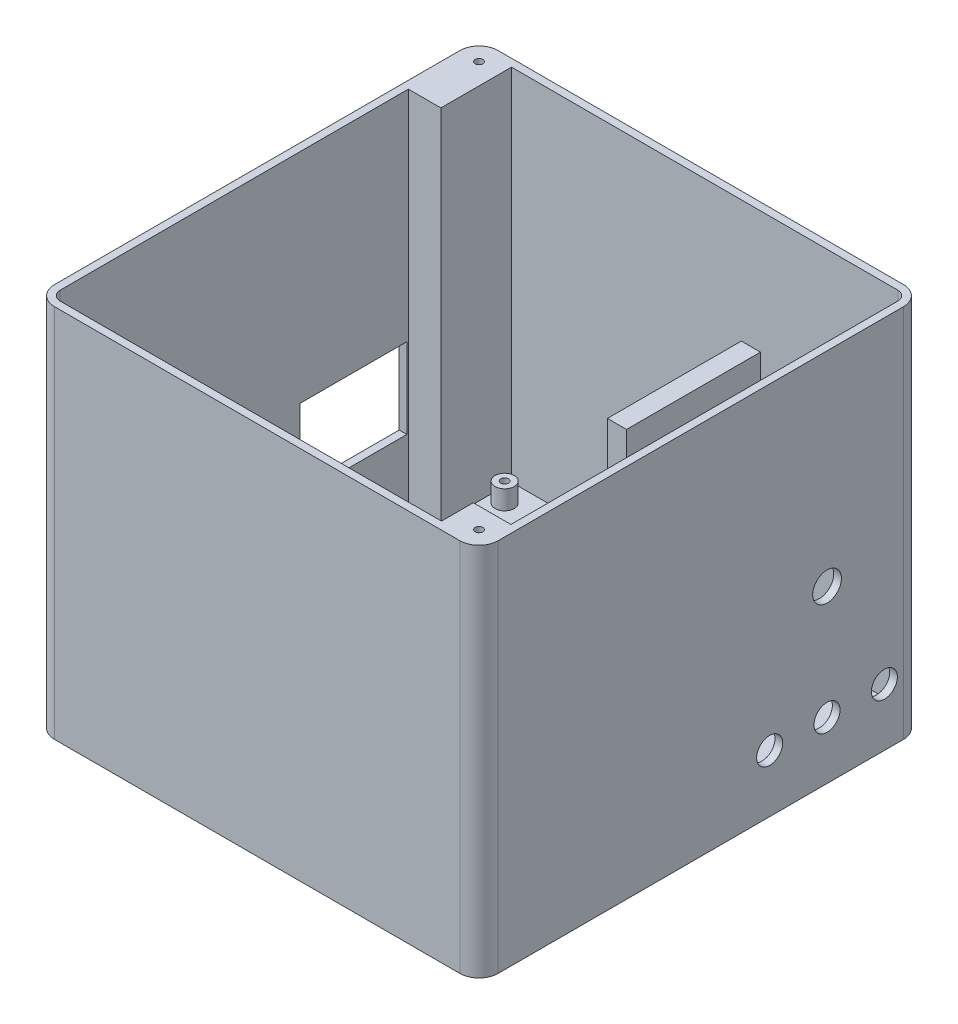
SolidWorks part; units mm, degrees
ref_plane "Front Plane" through (0, 0, 0) normal (0, 0, 1) x (1, 0, 0)
ref_plane "Top Plane" through (0, 0, 0) normal (0, 1, 0) x (1, 0, 0)
ref_plane "Right Plane" through (0, 0, 0) normal (1, 0, 0) x (0, 0, -1)
sketch "Sketch3" plane through (0, 0, 0) normal (0, 1, 0) x (1, 0, 0)
  line L1 (56, 56) -> (-56, 56)
  line L2 (56, 56) -> (56, -56)
  line L3 (56, -56) -> (-56, -56)
  line L4 (-56, 56) -> (-56, -56)
  line L5 (56, 56) -> (-56, -56) construction
  line L6 (56, -56) -> (-56, 56) construction
  point P0 (0, 0)
  dimension "D1" = 112
  dimension "D2" = 112
extrude "Extrude-Thin1" add sketch "Sketch3" along normal blind 98 thin
sketch "Sketch7" plane through (-56, 0, 0) normal (1, 0, 0) x (0, 0, -1)
  line L0 (56, 98) -> (56, 0) construction
  line L1 (-56, 0) -> (56, 0)
  line L2 (-56, 0) -> (-56, 4)
  line L3 (-56, 4) -> (56, 4)
  line L4 (56, 0) -> (56, 4)
  line L5 (56, 0) -> (-56, 0) construction
  dimension "D1" = 4
extrude "Boss-Extrude1" add sketch "Sketch7" along normal up to surface (112 mm away) up to face at (56, 49, 0)
sketch "Sketch13" plane through (0, 4, 0) normal (0, 1, 0) x (1, 0, 0)
  line L1 (39.1589, 5.1688) -> (-53.8411, 5.1688)
  line L2 (39.1589, 5.1688) -> (39.1589, -54.8312)
  line L3 (39.1589, -54.8312) -> (-53.8411, -54.8312)
  line L4 (-53.8411, 5.1688) -> (-53.8411, -54.8312)
  line L5 (39.1589, 5.1688) -> (-53.8411, -54.8312) construction
  line L6 (39.1589, -54.8312) -> (-53.8411, 5.1688) construction
  point P0 (-7.3411, -24.8312)
  dimension "D1" = 60
  dimension "D2" = 93
sketch "Sketch15" plane through (0, 4, 0) normal (0, 1, 0) x (1, 0, 0)
  line L1 (10.8366, 52.9269) -> (-46.1634, 52.9269)
  line L2 (10.8366, 52.9269) -> (10.8366, 9.3669)
  line L3 (10.8366, 9.3669) -> (-46.1634, 9.3669)
  line L4 (-46.1634, 52.9269) -> (-46.1634, 9.3669)
  line L5 (10.8366, 52.9269) -> (-46.1634, 9.3669) construction
  line L6 (10.8366, 9.3669) -> (-46.1634, 52.9269) construction
  point P0 (-17.6634, 31.1469)
  dimension "D1" = 57
  dimension "D2" = 43.56
sketch "Sketch16" plane through (0, 4, 0) normal (0, 1, 0) x (1, 0, 0)
  line L0 (-46.1634, 52.9269) -> (-46.1634, 9.3669) construction
  line L1 (10.8366, 9.3669) -> (-46.1634, 9.3669) construction
  circle A0 centre (-43.6634, 11.8669) radius 2.5
  circle A1 centre (8.3366, 11.8669) radius 2.5
  circle A2 centre (8.3366, 50.3669) radius 2.5
  circle A3 centre (-43.6634, 50.3669) radius 2.5
  dimension "D3" = 5
  dimension "D1" = 2.5
  dimension "D2" = 2.5
  dimension "D4" = 2
  dimension "D5" = 2
extrude "Boss-Extrude5" add sketch "Sketch16" along normal blind 5
sketch "Sketch17" plane through (0, 9, 0) normal (0, 1, 0) x (1, 0, 0)
  circle A0 centre (8.3366, 11.8669) radius 1
  circle A1 centre (-43.6634, 11.8669) radius 1
  circle A2 centre (-43.6634, 50.3669) radius 1
  circle A3 centre (8.3366, 50.3669) radius 1
  dimension "D1" = 2
  dimension "D2" = 2
  dimension "D3" = 2
extrude "Cut-Extrude1" cut sketch "Sketch17" against normal blind 10
sketch "Sketch24" plane through (-58, 0, 0) normal (-1, 0, 0) x (0, 0, 1)
  line L1 (-37.1281, 41) -> (-9.1281, 41)
  line L2 (-37.1281, 41) -> (-37.1281, 20)
  line L3 (-37.1281, 20) -> (-9.1281, 20)
  line L4 (-9.1281, 41) -> (-9.1281, 20)
  line L5 (-37.1281, 41) -> (-9.1281, 20) construction
  line L6 (-37.1281, 20) -> (-9.1281, 41) construction
  line L8 (-58, 0) -> (58, 0) construction
  point P0 (-23.1281, 30.5)
  dimension "D1" = 28
  dimension "D2" = 21
  dimension "D3" = 20
extrude "Cut-Extrude5" cut sketch "Sketch24" against normal blind 3
sketch "Sketch25" plane through (58, 0, 0) normal (1, 0, 0) x (0, 0, -1)
  line L0 (58, 0) -> (58, 15)
  line L1 (58, 98) -> (58, 0) construction
  circle A0 centre (48, 15) radius 3.4
  circle A1 centre (33, 15) radius 3.4
  circle A2 centre (18, 15) radius 3.4
  dimension "D2" = 6.8
  dimension "D3" = 6.8
  dimension "D4" = 6.8
  dimension "D1" = 15
  dimension "D5" = 10
  dimension "D6" = 15
  dimension "D7" = 15
extrude "Cut-Extrude6" cut sketch "Sketch25" against normal blind 5 contours A2 | A1 | A0
sketch "Sketch26" plane through (-58, 0, 0) normal (-1, 0, 0) x (0, 0, 1)
  line L1 (-37.1281, 41) -> (-9.1281, 41)
  line L2 (-37.1281, 41) -> (-37.1281, 20)
  line L3 (-37.1281, 20) -> (-9.1281, 20)
  line L4 (-9.1281, 41) -> (-9.1281, 20)
  line L5 (1.8719, 42.1305) -> (-48.1281, 42.1305)
  line L6 (1.8719, 42.1305) -> (1.8719, 19.1305)
  line L7 (1.8719, 19.1305) -> (-48.1281, 19.1305)
  line L8 (-48.1281, 42.1305) -> (-48.1281, 19.1305)
  line L9 (1.8719, 42.1305) -> (-48.1281, 19.1305) construction
  line L10 (1.8719, 19.1305) -> (-48.1281, 42.1305) construction
  circle A0 centre (-42.7671, 30.6305) radius 2
  circle A1 centre (-2.7671, 30.6305) radius 2
  point P6 (-23.1281, 30.6305)
  dimension "D3" = 4
  dimension "D4" = 4
  dimension "D1" = 50
  dimension "D2" = 23
  dimension "D5" = 40
extrude "Cut-Extrude7" cut sketch "Sketch26" against normal blind 10 contours A0 | A1
fillet "Fillet1" radius 5 4 edges at (-58, 49, 58) (-58, 49, -58) (58, 49, -58) (58, 49, 58)
sketch "Sketch28" plane through (0, 0, 0) normal (0, -1, 0) x (1, 0, 0)
  circle A0 centre (-53.8411, 54.8312) radius 1
  circle A1 centre (-43.8411, 54.8312) radius 1
  circle A2 centre (-33.8411, 54.8312) radius 1
  circle A3 centre (-23.8411, 54.8312) radius 1
  circle A4 centre (-13.8411, 54.8312) radius 1
  circle A5 centre (-3.8411, 54.8312) radius 1
  circle A6 centre (6.1589, 54.8312) radius 1
  circle A7 centre (16.1589, 54.8312) radius 1
  circle A8 centre (26.1589, 54.8312) radius 1
  circle A9 centre (36.1589, 54.8312) radius 1
  circle A10 centre (-43.8411, 44.8312) radius 1
  circle A11 centre (-33.8411, 44.8312) radius 1
  circle A12 centre (-23.8411, 44.8312) radius 1
  circle A13 centre (-13.8411, 44.8312) radius 1
  circle A14 centre (-3.8411, 44.8312) radius 1
  circle A15 centre (6.1589, 44.8312) radius 1
  circle A16 centre (16.1589, 44.8312) radius 1
  circle A17 centre (26.1589, 44.8312) radius 1
  circle A18 centre (36.1589, 44.8312) radius 1
  circle A19 centre (-43.8411, 34.8312) radius 1
  circle A20 centre (-33.8411, 34.8312) radius 1
  circle A21 centre (-23.8411, 34.8312) radius 1
  circle A22 centre (-13.8411, 34.8312) radius 1
  circle A23 centre (-3.8411, 34.8312) radius 1
  circle A24 centre (6.1589, 34.8312) radius 1
  circle A25 centre (16.1589, 34.8312) radius 1
  circle A26 centre (26.1589, 34.8312) radius 1
  circle A27 centre (36.1589, 34.8312) radius 1
  circle A28 centre (-43.8411, 24.8312) radius 1
  circle A29 centre (-33.8411, 24.8312) radius 1
  circle A30 centre (-23.8411, 24.8312) radius 1
  circle A31 centre (-13.8411, 24.8312) radius 1
  circle A32 centre (-3.8411, 24.8312) radius 1
  circle A33 centre (6.1589, 24.8312) radius 1
  circle A34 centre (16.1589, 24.8312) radius 1
  circle A35 centre (26.1589, 24.8312) radius 1
  circle A36 centre (36.1589, 24.8312) radius 1
  circle A37 centre (-43.8411, 14.8312) radius 1
  circle A38 centre (-33.8411, 14.8312) radius 1
  circle A39 centre (-23.8411, 14.8312) radius 1
  circle A40 centre (-13.8411, 14.8312) radius 1
  circle A41 centre (-3.8411, 14.8312) radius 1
  circle A42 centre (6.1589, 14.8312) radius 1
  circle A43 centre (16.1589, 14.8312) radius 1
  circle A44 centre (26.1589, 14.8312) radius 1
  circle A45 centre (36.1589, 14.8312) radius 1
  circle A46 centre (-43.8411, 4.8312) radius 1
  circle A47 centre (-33.8411, 4.8312) radius 1
  circle A48 centre (-23.8411, 4.8312) radius 1
  circle A49 centre (-13.8411, 4.8312) radius 1
  circle A50 centre (-3.8411, 4.8312) radius 1
  circle A51 centre (6.1589, 4.8312) radius 1
  circle A52 centre (16.1589, 4.8312) radius 1
  circle A53 centre (26.1589, 4.8312) radius 1
  circle A54 centre (36.1589, 4.8312) radius 1
  circle A55 centre (-43.8411, -5.1688) radius 1
  circle A56 centre (-33.8411, -5.1688) radius 1
  circle A57 centre (-23.8411, -5.1688) radius 1
  circle A58 centre (-13.8411, -5.1688) radius 1
  circle A59 centre (-3.8411, -5.1688) radius 1
  circle A60 centre (6.1589, -5.1688) radius 1
  circle A61 centre (16.1589, -5.1688) radius 1
  circle A62 centre (26.1589, -5.1688) radius 1
  circle A63 centre (36.1589, -5.1688) radius 1
  circle A64 centre (-53.8411, 44.8312) radius 1
  circle A65 centre (-53.8411, 34.8312) radius 1
  circle A66 centre (-53.8411, 24.8312) radius 1
  circle A67 centre (-53.8411, 14.8312) radius 1
  circle A68 centre (-53.8411, 4.8312) radius 1
  circle A69 centre (-53.8411, -5.1688) radius 1
  dimension "D1" = 2
  dimension "D2" = 10
  dimension "D3" = 7
extrude "Cut-Extrude8" cut sketch "Sketch28" against normal blind 5
sketch "Sketch29" plane through (0, 4, 0) normal (0, 1, 0) x (1, 0, 0)
  line L0 (39.1589, 5.1688) -> (30.0023, 5.1688)
  line L1 (39.1589, 5.1688) -> (-53.8411, 5.1688) construction
  line L2 (30.0023, 5.1688) -> (30.0023, 9.7954)
  line L3 (30.0023, 9.7954) -> (53.3852, 9.7954)
  line L4 (53.3852, 9.7954) -> (53.3852, -6.0279)
  line L5 (53.3852, -6.0279) -> (39.1589, -6.0279)
  line L6 (39.1589, 5.1688) -> (39.1589, -54.8312) construction
  line L7 (39.1589, -6.0279) -> (39.1589, 5.1688)
  line L8 (39.1589, -6.1727) -> (56.512, -6.1727)
  line L9 (56.512, -6.1727) -> (56.512, -56)
  line L10 (-56, -56) -> (56, -56) construction
  line L11 (56.512, -56) -> (39.1589, -56)
  line L12 (39.1589, -56) -> (39.1589, -6.1727)
extrude "Boss-Extrude7" add sketch "Sketch29" along normal blind 62
sketch "Sketch31" plane through (56, 0, 0) normal (-1, 0, 0) x (0, 0, 1)
  line L1 (-42.25, 19.4) -> (-53.75, 19.4)
  line L2 (-42.25, 19.4) -> (-42.25, 10.6)
  line L3 (-42.25, 10.6) -> (-53.75, 10.6)
  line L4 (-53.75, 19.4) -> (-53.75, 10.6)
  line L5 (-42.25, 19.4) -> (-53.75, 10.6) construction
  line L6 (-42.25, 10.6) -> (-53.75, 19.4) construction
  line L7 (-27.25, 19.4) -> (-38.75, 19.4)
  line L8 (-27.25, 19.4) -> (-27.25, 10.6)
  line L9 (-27.25, 10.6) -> (-38.75, 10.6)
  line L10 (-38.75, 19.4) -> (-38.75, 10.6)
  line L11 (-27.25, 19.4) -> (-38.75, 10.6) construction
  line L12 (-27.25, 10.6) -> (-38.75, 19.4) construction
  line L13 (-12.25, 19.4) -> (-23.75, 19.4)
  line L14 (-12.25, 19.4) -> (-12.25, 10.6)
  line L15 (-12.25, 10.6) -> (-23.75, 10.6)
  line L16 (-23.75, 19.4) -> (-23.75, 10.6)
  line L17 (-12.25, 19.4) -> (-23.75, 10.6) construction
  line L18 (-12.25, 10.6) -> (-23.75, 19.4) construction
  point P0 (-48, 15)
  point P6 (-33, 15)
  point P12 (-18, 15)
  dimension "D1" = 11.5
  dimension "D2" = 8.8
  dimension "D3" = 8.8
  dimension "D4" = 8.8
  dimension "D5" = 11.5
  dimension "D6" = 11.5
sketch "Sketch32" plane through (0, 4, 0) normal (0, 1, 0) x (1, 0, 0)
  line L0 (56, -6.1727) -> (56, 56) construction
  line L1 (56, 55.4385) -> (41.5, 55.4385)
  line L2 (56, 55.4385) -> (56, 43.9385)
  line L3 (56, 43.9385) -> (41.5, 43.9385)
  line L4 (41.5, 55.4385) -> (41.5, 43.9385)
  line L5 (56, 12.25) -> (56, 23.75) construction
  line L6 (41.5, 24.75) -> (56, 24.75)
  line L7 (41.5, 24.75) -> (41.5, 13.25)
  line L8 (41.5, 13.25) -> (56, 13.25)
  line L9 (56, 24.75) -> (56, 13.25)
  line L10 (56, -56) -> (56, 56) construction
  line L11 (56, 27.25) -> (56, 38.75) construction
  line L12 (41.5, 39.75) -> (56, 39.75)
  line L13 (41.5, 39.75) -> (41.5, 28.25)
  line L14 (41.5, 28.25) -> (56, 28.25)
  line L15 (56, 39.75) -> (56, 28.25)
  line L16 (56, 27.25) -> (56, 38.75) construction
  dimension "D1" = 11.5
  dimension "D2" = 14.5
  dimension "D3" = 14.5
sketch "Sketch37" plane through (56, 0, 0) normal (-1, 0, 0) x (0, 0, 1)
  line L0 (6.1727, 66) -> (56, 66) construction
  line L1 (44, 66) -> (-56, 66)
  line L2 (44, 66) -> (44, 70.1073)
  line L3 (44, 70.1073) -> (-56, 70.1073)
  line L4 (-56, 66) -> (-56, 70.1073)
  line L5 (-56, 98) -> (-56, 4) construction
  dimension "D1" = 100
sketch "Sketch38" plane through (0, 66, 0) normal (0, 1, 0) x (1, 0, 0)
  line L7 (56, -56) -> (56, 56) construction
  line L8 (56, -45.5) -> (-37, -45.5)
  line L9 (56, -45.5) -> (56, 54.5)
  line L10 (56, 54.5) -> (-37, 54.5)
  line L11 (-37, -45.5) -> (-37, 54.5)
  line L12 (56, 56) -> (-56, 56) construction
  circle A0 centre (54.2, -43.7) radius 1
  dimension "D4" = 2
  dimension "D1" = 93
  dimension "D2" = 100
  dimension "D3" = 1.5
  dimension "D5" = 1.8
  dimension "D6" = 1.8
sketch "Sketch39" plane through (0, 4, 0) normal (0, 1, 0) x (1, 0, 0)
  line L5 (56, 56) -> (-56, 56) construction
  line L6 (12.5923, 56) -> (17.5923, 56)
  line L7 (12.5923, 56) -> (12.5923, 20.9871)
  line L8 (12.5923, 20.9871) -> (17.5923, 20.9871)
  line L9 (17.5923, 56) -> (17.5923, 20.9871)
  dimension "D1" = 5
extrude "Boss-Extrude9" add sketch "Sketch39" along normal up to surface (62 mm away) up to face at (47.5795, 66, 31.0863)
extrude "Cut-Extrude9" cut sketch "Sketch38" against normal blind 10 contours A0
sketch "Sketch40" plane through (0, 66, 0) normal (0, 1, 0) x (1, 0, 0)
  line L0 (54.2, -43.7) -> (54.2, -45.5)
  line L1 (39.1589, -6.1727) -> (39.1589, -56) construction
  line L2 (56, -56) -> (39.1589, -56)
  line L3 (56, -56) -> (56, -47.6554)
  line L4 (56, -47.6554) -> (39.1589, -47.6554)
  line L5 (39.1589, -56) -> (39.1589, -47.6554)
  line M3 (56, -56) -> (56, -6.1727)
  line M5 (39.1589, -6.1727) -> (39.1589, -56)
  line M6 (39.1589, -56) -> (56, -56)
  dimension "D1" = 1.8
extrude "Boss-Extrude10" add sketch "Sketch40" along normal up to vertex (32 mm away) contours L4 M3 M5 M6
sketch "Sketch41" plane through (0, 66, 0) normal (0, 1, 0) x (1, 0, 0)
  line L0 (56, -6.1727) -> (56, -47.6554) construction
  line L1 (56, -45.5) -> (-37, -45.5)
  line L2 (56, -45.5) -> (56, 54.5)
  line L3 (56, 54.5) -> (-37, 54.5)
  line L4 (-37, -45.5) -> (-37, 54.5)
  line L5 (56, 56) -> (-56, 56) construction
  dimension "D1" = 93
  dimension "D2" = 100
  dimension "D3" = 1.5
sketch "Sketch42" plane through (0, 4, 0) normal (0, 1, 0) x (1, 0, 0)
  line L1 (-56, 56) -> (-47.4925, 56)
  line L2 (-56, 56) -> (-56, 37.5299)
  line L3 (-56, 37.5299) -> (-47.4925, 37.5299)
  line L4 (-47.4925, 56) -> (-47.4925, 37.5299)
extrude "Boss-Extrude11" add sketch "Sketch42" along normal up to vertex (94 mm away)
fillet "Fillet3" radius 2.5 2 edges at (-56, 51, 56) (56, 51, -56)
sketch "Sketch44" plane through (0, 98, 0) normal (0, 1, 0) x (1, 0, 0)
  line L0 (53, 58) -> (-53, 58) construction
  line L1 (-58, 53) -> (-58, -53) construction
  line L2 (-53, -58) -> (53, -58) construction
  line L3 (58, -53) -> (58, 53) construction
  circle A0 centre (53, -53) radius 1
  circle A1 centre (-53, 53) radius 1
  dimension "D1" = 2
  dimension "D2" = 2
  dimension "D3" = 5
  dimension "D4" = 5
  dimension "D5" = 5
  dimension "D6" = 5
extrude "Cut-Extrude10" cut sketch "Sketch44" against normal blind 10
sketch "Sketch49" plane through (58, 0, 0) normal (1, 0, 0) x (0, 0, -1)
  circle A0 centre (33.0088, 44.6265) radius 3.75
  dimension "D1" = 7.5
extrude "Cut-Extrude11" cut sketch "Sketch49" against normal blind 5
sketch "Sketch53" plane through (0, 66, 0) normal (0, 1, 0) x (1, 0, 0)
  line L1 (39.1589, 5.1688) -> (46.1589, 5.1688)
  line L2 (39.1589, 5.1688) -> (39.1589, -55.9585)
  line L3 (39.1589, -55.9585) -> (46.1589, -55.9585)
  line L4 (46.1589, 5.1688) -> (46.1589, -55.9585)
  dimension "D1" = 7
extrude "Cut-Extrude13" cut sketch "Sketch53" against normal up to surface and the other way through all
